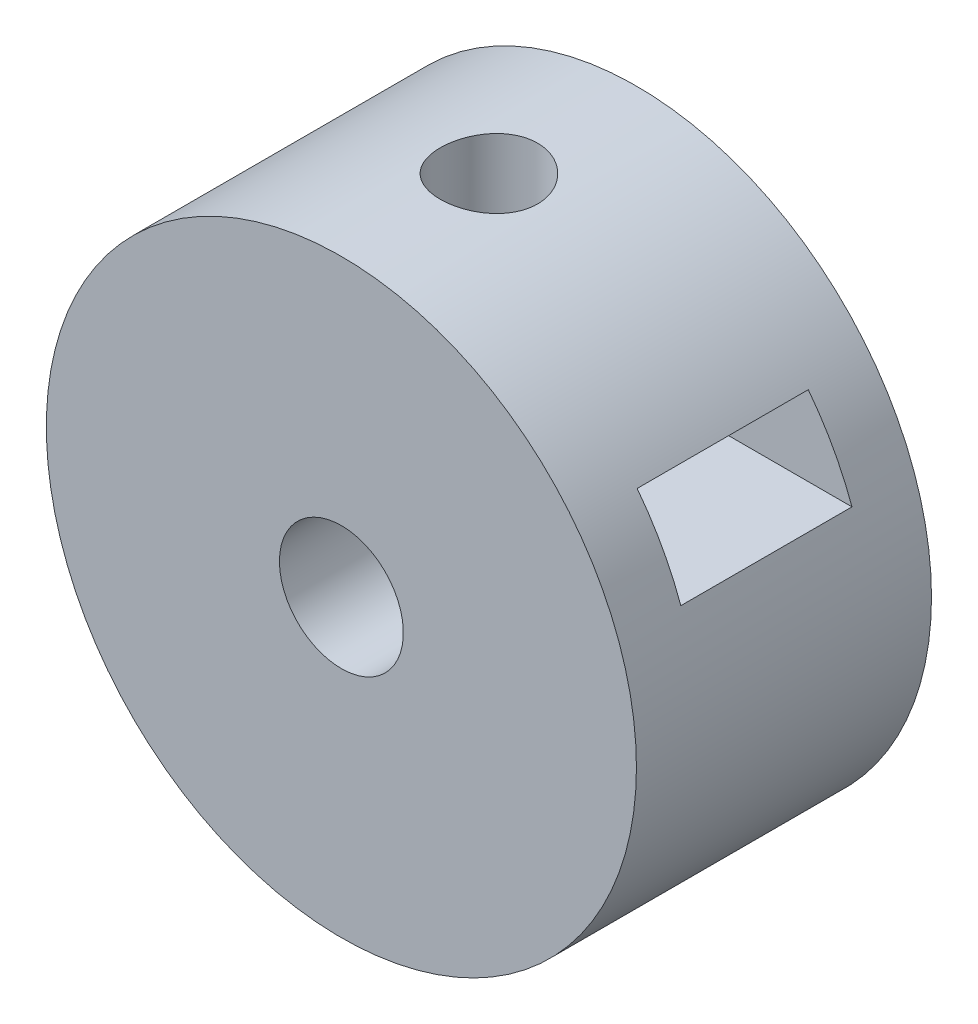
SolidWorks part; units mm, degrees
ref_plane "Спереди" through (0, 0, 0) normal (0, 0, 1) x (1, 0, 0)
ref_plane "Сверху" through (0, 0, 0) normal (0, 1, 0) x (1, 0, 0)
ref_plane "Справа" through (0, 0, 0) normal (1, 0, 0) x (0, 0, -1)
sketch "Эскиз1" plane through (0, 0, 0) normal (0, 0, 1) x (1, 0, 0)
  circle A0 centre (0, 0) radius 10
  dimension "D1" = 20
extrude "Бобышка-Вытянуть1" add sketch "Эскиз1" along normal blind 10
sketch "Эскиз2" plane through (0, 0, 0) normal (0, 0, -1) x (-1, 0, 0)
  circle A0 centre (0, 0) radius 2.1
  dimension "D1" = 4.2
extrude "Вырез-Вытянуть2" cut sketch "Эскиз2" against normal blind 10
ref_plane "Плоскость4" through (10, 0, 0) normal (1, 0, 0) x (0, 0, -1)
sketch3d "Трехмерный эскиз4"
  line L1 (10, 6.1, 7.9) -> (10, 6.1, 2.1)
  line L2 (10, 6.1, 7.9) -> (10, 3.4, 7.9)
  line L3 (10, 3.4, 7.9) -> (10, 3.4, 2.1)
  line L4 (10, 6.1, 2.1) -> (10, 3.4, 2.1)
  circle A0 centre (0, 0, 10) radius 2.1 construction
  point P6 (0, 0, 7.9)
  point P7 (10, 0, 10)
  point P8 (10, 4.75, 7.9)
  point P9 (10, 0, 10)
  dimension "D1" = 2.7
  dimension "D2" = 5.8
  dimension "D3" = 2.1
  dimension "D4" = 3.4
extrude "Вырез-Вытянуть3" cut sketch "Трехмерный эскиз4" along direction (1, 0, 0) on the side against the normal blind 10
ref_plane "Плоскость5" through (0, 10, 0) normal (0, 1, 0) x (1, 0, 0)
sketch "Эскиз5" plane through (0, 10, 0) normal (0, 1, 0) x (1, 0, 0)
  line L0 (10, 0) -> (-10, 0) construction
  circle A0 centre (0, -5) radius 1.65
  point P2 (0, -4.867)
  dimension "D1" = 3.3
  dimension "D2" = 5
extrude "Вырез-Вытянуть4" cut sketch "Эскиз5" against normal blind 10
sketch "Эскиз6" plane through (0, 10, 0) normal (0, 1, 0) x (1, 0, 0)
  line L1 (-1.6743, -2.1) -> (-3.3486, -5)
  line L2 (-3.3486, -5) -> (-1.6743, -7.9)
  line L3 (-1.6743, -7.9) -> (1.6743, -7.9)
  line L4 (1.6743, -7.9) -> (3.3486, -5)
  line L5 (3.3486, -5) -> (1.6743, -2.1)
  line L6 (1.6743, -2.1) -> (-1.6743, -2.1)
  line L7 (3.3486, -5) -> (-3.3486, -5) construction
  line L8 (7.924, -2.1) -> (7.924, -7.9) construction
  circle A0 centre (0, -5) radius 2.9 construction
  point P10 (-3.7925, -4.8553)
  dimension "D1" = 5.8
  dimension "D2" = 5
extrude "Вырез-Вытянуть5" cut sketch "Эскиз6" along direction (0, 1, 0) on the side against the normal blind 2.7 from offset 3.9 contours L1 L2 L3 L4 L5 L6 offset against normal yes
